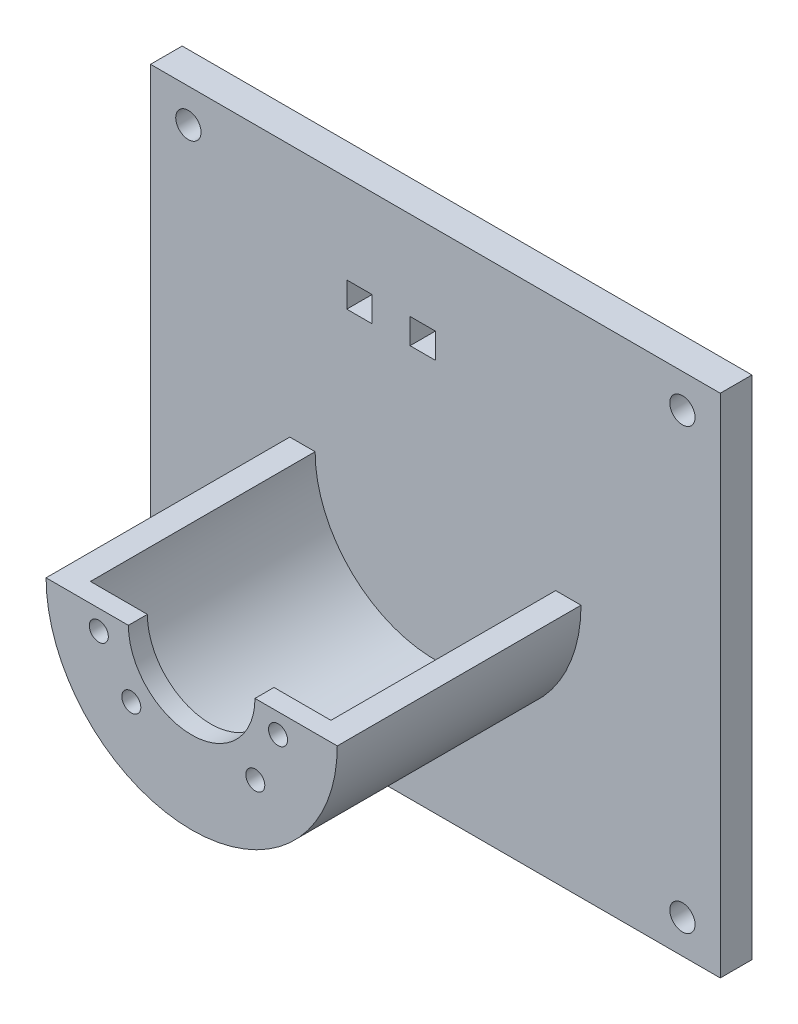
SolidWorks part; units mm, degrees
ref_plane "Front Plane" through (0, 0, 0) normal (0, 0, 1) x (1, 0, 0)
ref_plane "Top Plane" through (0, 0, 0) normal (0, 1, 0) x (1, 0, 0)
ref_plane "Right Plane" through (0, 0, 0) normal (1, 0, 0) x (0, 0, -1)
sketch "Sketch1" plane through (0, 0, 0) normal (0, 0, 1) x (1, 0, 0)
  line L0 (-19, 0) -> (19, 0) construction
  line L1 (-23, 0) -> (-19, 0)
  line L2 (19, 0) -> (23, 0)
  arc A0 (-19, 0) -> (19, 0) centre (0, 0) ccw
  arc A1 (-23, 0) -> (23, 0) centre (0, 0) ccw
  dimension "D1" = 19
  dimension "D2" = 23
extrude "Boss-Extrude1" add sketch "Sketch1" along normal blind 35.5 contours A0 L2 A1 L1
sketch "Sketch2" plane through (0, 0, 0) normal (0, 0, -1) x (-1, 0, 0)
  line L0 (0, 12.65) -> (0, -12.65) construction
  line L1 (-45, 40) -> (45, 40)
  line L2 (-45, 40) -> (-45, -40)
  line L3 (-45, -40) -> (45, -40)
  line L4 (45, 40) -> (45, -40)
  line L5 (-45, 40) -> (45, -40) construction
  line L6 (-45, -40) -> (45, 40) construction
  line L7 (19.525, 0) -> (-19.525, 0) construction
  circle A0 centre (-39.0207, 34.6851) radius 2
  circle A1 centre (39.0207, 34.6851) radius 2
  circle A2 centre (39.0207, -34.6851) radius 2
  circle A3 centre (-39.0207, -34.6851) radius 2
  point P0 (0, 0)
  line M5 (23, 0) -> (19, 0)
  arc M6 (19, 0) -> (-19, 0) centre (0, 0) cw
  line M7 (-19, 0) -> (-23, 0)
  arc M8 (-23, 0) -> (23, 0) centre (0, 0) ccw
  dimension "D3" = 4
  dimension "D1" = 80
  dimension "D2" = 90
  dimension "D4" = 8
extrude "Boss-Extrude2" add sketch "Sketch2" along normal blind 5 contours L4 L1 L2 L3 A1 A0 A2 A3 M5 M8 M7 M6 | M8 M5 M6 M7
sketch "Sketch3" plane through (0, 0, 35.5) normal (0, 0, 1) x (1, 0, 0)
  line L0 (-23, 0) -> (-10, 0)
  line L1 (10, 0) -> (23, 0)
  arc A0 (-10, 0) -> (10, 0) centre (0, 0) ccw
  arc A1 (-23, 0) -> (23, 0) centre (0, 0) ccw
  arc A2 (-23, 0) -> (23, 0) centre (0, 0) ccw construction
  arc A3 (-23, 0) -> (23, 0) centre (0, 0) ccw construction
  dimension "D1" = 10
  dimension "D2" = 13
extrude "Boss-Extrude3" add sketch "Sketch3" along normal blind 3
sketch "Sketch4" plane through (0, 0, 38.5) normal (0, 0, 1) x (1, 0, 0)
  line L0 (10.049, -11.1363) -> (0, 0) construction
  line L1 (0, 0) -> (13.6446, -3.1346) construction
  circle A0 centre (-9.5369, -10.2493) radius 1.5
  circle A1 centre (-4.1077, 13.3838) radius 1.5 construction
  circle A2 centre (13.6446, -3.1346) radius 1.5
  circle A3 centre (10.049, -11.1363) radius 1.5
  circle A4 centre (4.6198, 14.2709) radius 1.5 construction
  circle A5 centre (-14.6688, -3.1346) radius 1.5
  point P2 (0, 0)
  point P9 (0, 0)
  point P17 (0, 0)
  dimension "D1" = 3
  dimension "D4" = 3
  dimension "D3" = 14
  dimension "D6" = 15
  dimension "D7" = 35
  dimension "D2" = 3
  dimension "D5" = 3
extrude "Cut-Extrude1" cut sketch "Sketch4" against normal up to surface (3 mm away) up to face at (0, -7.25, 35.5)
sketch "Sketch5" plane through (0, 0, 0) normal (0, 0, 1) x (1, 0, 0)
  line L0 (0.5249, 0) -> (0, 0) construction
  line L1 (0, 0) -> (0, 33.6686) construction
  line L2 (-10, 0) -> (-23, 0) construction
  line L3 (-14, 26) -> (-10, 26)
  line L4 (-14, 26) -> (-14, 22)
  line L5 (-14, 22) -> (-10, 22)
  line L6 (-10, 26) -> (-10, 22)
  line L7 (-4, 26) -> (-4, 22)
  line L8 (-4, 26) -> (0, 26)
  line L9 (0, 26) -> (0, 22)
  line L10 (-4, 22) -> (0, 22)
  dimension "D1" = 4
  dimension "D2" = 4
  dimension "D3" = 10
  dimension "D4" = 22
  dimension "D5" = 2
extrude "Cut-Extrude2" cut sketch "Sketch5" against normal through all
